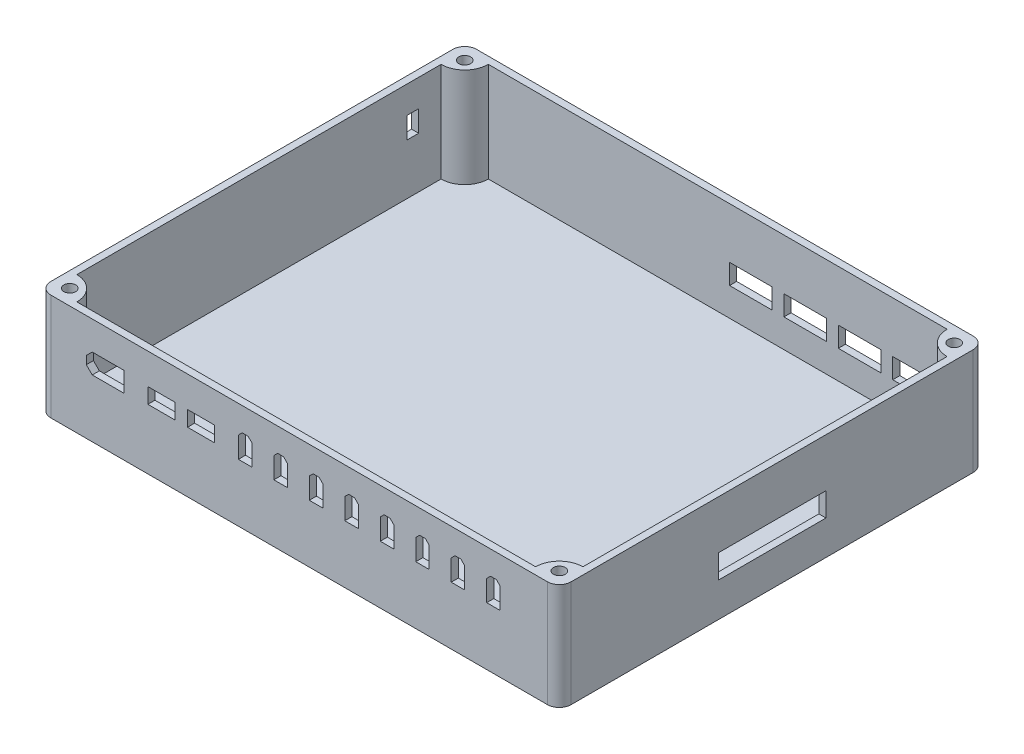
SolidWorks part; units mm, degrees
ref_plane "Front Plane" through (0, 0, 0) normal (0, 0, 1) x (1, 0, 0)
ref_plane "Top Plane" through (0, 0, 0) normal (0, 1, 0) x (1, 0, 0)
ref_plane "Right Plane" through (0, 0, 0) normal (1, 0, 0) x (0, 0, -1)
sketch "Sketch1" plane through (0, 0, 0) normal (0, 1, 0) x (1, 0, 0)
  line L1 (0, 0) -> (220, 0)
  line L2 (0, 0) -> (0, 180)
  line L3 (0, 180) -> (220, 180)
  line L4 (220, 0) -> (220, 180)
  dimension "D1" = 220
  dimension "D2" = 180
extrude "Boss-Extrude1" add sketch "Sketch1" along normal blind 45
fillet "Fillet1" radius 5 4 edges at (0, 22.5, -180) (0, 22.5, 0) (220, 22.5, -180) (220, 22.5, 0)
sketch "Sketch7" plane through (0, 45, 0) normal (0, 1, 0) x (1, 0, 0)
  line L0 (110, 187.4123) -> (110, -2.139) construction
  line L1 (-6.8646, 90) -> (231.1986, 90) construction
  line L2 (207, 177) -> (13, 177)
  line L3 (217, 167) -> (217, 13)
  line L4 (215, 180) -> (5, 180) construction
  line L5 (220, 5) -> (220, 175) construction
  line L6 (207, 3) -> (13, 3)
  line L7 (3, 167) -> (3, 13)
  line L8 (0, 175) -> (0, 5) construction
  line L9 (5, 0) -> (215, 0) construction
  arc A0 (207, 177) -> (217, 167) centre (217, 177) ccw
  arc A1 (207, 3) -> (217, 13) centre (217, 3) cw
  arc A2 (13, 3) -> (3, 13) centre (3, 3) ccw
  arc A3 (13, 177) -> (3, 167) centre (3, 177) cw
  point P14 (217, 90)
  point P18 (110, 3)
  point P23 (110, 177)
  dimension "D5" = 3
  dimension "D1" = 3
  dimension "D2" = 3
  dimension "D3" = 13
  dimension "D4" = 13
  dimension "D6" = 3
extrude "Cut-Extrude7" cut sketch "Sketch7" against normal blind 42
sketch "Sketch2" plane through (0, 0, 0) normal (0, 0, 1) x (1, 0, 0)
  line L0 (175.9, 35) -> (178.4, 35)
  line L1 (190.9, 35) -> (193.4, 35)
  line L2 (189.3, 33.4) -> (189.3, 24.5)
  line L3 (189.3, 24.5) -> (195, 24.5)
  line L4 (195, 33.4) -> (195, 24.5)
  line L5 (174.3, 33.4) -> (174.3, 24.5)
  line L6 (174.3, 24.5) -> (180, 24.5)
  line L7 (180, 33.4) -> (180, 24.5)
  line L8 (160.9, 35) -> (163.4, 35)
  line L9 (159.3, 33.4) -> (159.3, 24.5)
  line L10 (159.3, 24.5) -> (165, 24.5)
  line L11 (165, 33.4) -> (165, 24.5)
  line L12 (145.9, 35) -> (148.4, 35)
  line L13 (144.3, 33.4) -> (144.3, 24.5)
  line L14 (144.3, 24.5) -> (150, 24.5)
  line L15 (150, 33.4) -> (150, 24.5)
  line L16 (130.9, 35) -> (133.4, 35)
  line L17 (129.3, 33.4) -> (129.3, 24.5)
  line L18 (129.3, 24.5) -> (135, 24.5)
  line L19 (135, 33.4) -> (135, 24.5)
  line L20 (115.9, 35) -> (118.4, 35)
  line L21 (114.3, 33.4) -> (114.3, 24.5)
  line L22 (114.3, 24.5) -> (120, 24.5)
  line L23 (120, 33.4) -> (120, 24.5)
  line L24 (100.9, 35) -> (103.4, 35)
  line L25 (99.3, 33.4) -> (99.3, 24.5)
  line L26 (99.3, 24.5) -> (105, 24.5)
  line L27 (105, 33.4) -> (105, 24.5)
  line L28 (85.9, 35) -> (88.4, 35)
  line L29 (84.3, 33.4) -> (84.3, 24.5)
  line L30 (84.3, 24.5) -> (90, 24.5)
  line L31 (90, 33.4) -> (90, 24.5)
  line L33 (215, 0) -> (215, 45) construction
  line L35 (189.3, 33.4) -> (190.9, 35)
  line L36 (193.4, 35) -> (195, 33.4)
  line L37 (178.4, 35) -> (180, 33.4)
  line L38 (174.3, 33.4) -> (175.9, 35)
  line L39 (163.4, 35) -> (165, 33.4)
  line L40 (159.3, 33.4) -> (160.9, 35)
  line L41 (144.3, 33.4) -> (145.9, 35)
  line L42 (148.4, 35) -> (150, 33.4)
  line L43 (133.4, 35) -> (135, 33.4)
  line L44 (129.3, 33.4) -> (130.9, 35)
  line L45 (118.4, 35) -> (120, 33.4)
  line L46 (114.3, 33.4) -> (115.9, 35)
  line L47 (103.4, 35) -> (105, 33.4)
  line L48 (99.3, 33.4) -> (100.9, 35)
  line L49 (88.4, 35) -> (90, 33.4)
  line L50 (84.3, 33.4) -> (85.9, 35)
  point P0 (189.3, 35)
  point P3 (195, 35)
  point P6 (174.3, 35)
  point P9 (180, 35)
  point P10 (159.3, 35)
  point P13 (165, 35)
  point P14 (144.3, 35)
  point P17 (150, 35)
  point P18 (129.3, 35)
  point P21 (135, 35)
  point P22 (114.3, 35)
  point P25 (120, 35)
  point P26 (99.3, 35)
  point P29 (105, 35)
  point P30 (84.3, 35)
  point P33 (90, 35)
  dimension "D1" = 5.7
  dimension "D2" = 10.5
  dimension "D5" = 20
  dimension "D6" = 1.6
  dimension "D7" = 45
  dimension "D8" = 1.6
  dimension "D9" = 45
  dimension "D10" = 1.6
  dimension "D11" = 45
  dimension "D12" = 1.6
  dimension "D13" = 45
  dimension "D14" = 1.6
  dimension "D15" = 45
  dimension "D16" = 1.6
  dimension "D17" = 45
  dimension "D18" = 1.6
  dimension "D19" = 45
  dimension "D20" = 1.6
  dimension "D21" = 45
  dimension "D22" = 1.6
  dimension "D23" = 45
  dimension "D24" = 1.6
  dimension "D25" = 45
  dimension "D26" = 1.6
  dimension "D27" = 45
  dimension "D28" = 1.6
  dimension "D29" = 45
  dimension "D30" = 1.6
  dimension "D31" = 45
  dimension "D32" = 1.6
  dimension "D33" = 45
  dimension "D34" = 1.6
  dimension "D35" = 45
  dimension "D36" = 1.6
  dimension "D37" = 45
sketch "Sketch3" plane through (0, 0, 0) normal (0, 0, 1) x (1, 0, 0)
  line L0 (22.5, 32.9) -> (36, 32.9)
  line L1 (20, 30.4) -> (20, 27)
  line L2 (22.5, 24.5) -> (36, 24.5)
  line L3 (36, 32.9) -> (36, 24.5)
  line L4 (20, 30.4) -> (22.5, 32.9)
  line L5 (20, 27) -> (22.5, 24.5)
  line L6 (5, 0) -> (215, 0) construction
  line L7 (5, 45) -> (5, 0) construction
  point P0 (20, 32.9)
  point P2 (20, 24.5)
  dimension "D1" = 8.4
  dimension "D2" = 16
  dimension "D3" = 16
  dimension "D4" = 2.5
  dimension "D5" = 45
  dimension "D6" = 2.5
  dimension "D7" = 45
  dimension "D8" = 24.5
  dimension "D9" = 15
extrude "Cut-Extrude2" cut sketch "Sketch2" against normal blind 5
extrude "Cut-Extrude3" cut sketch "Sketch3" against normal blind 5
sketch "Sketch4" plane through (0, 0, 0) normal (0, 0, 1) x (1, 0, 0)
  line L0 (5, 0) -> (215, 0) construction
  line L1 (46, 25.5) -> (57.5, 25.5)
  line L2 (46, 25.5) -> (46, 32)
  line L3 (46, 32) -> (57.5, 32)
  line L4 (57.5, 25.5) -> (57.5, 32)
  line L5 (62.8, 25.5) -> (74.3, 25.5)
  line L6 (62.8, 25.5) -> (62.8, 32)
  line L7 (62.8, 32) -> (74.3, 32)
  line L8 (74.3, 25.5) -> (74.3, 32)
  line L9 (50.0473, 25.5) -> (65.0473, 25.5) construction
  line L10 (36, 24.5) -> (36, 32.9) construction
  line L11 (84.3, 33.4) -> (84.3, 24.5) construction
  dimension "D1" = 6.5
  dimension "D2" = 11.5
  dimension "D3" = 25.5
  dimension "D5" = 15
  dimension "D6" = 10
  dimension "D7" = 6.5
  dimension "D8" = 10
  dimension "D4" = 2
extrude "Cut-Extrude4" cut sketch "Sketch4" against normal blind 5
sketch "Sketch5" plane through (220, 0, 0) normal (1, 0, 0) x (0, 0, -1)
  line L0 (175, 0) -> (175, 45) construction
  line L5 (67.2316, 14.4802) -> (112.7684, 14.4802)
  line L7 (67.2316, 14.4802) -> (67.2316, 24.4802)
  line L8 (67.2316, 24.4802) -> (112.7684, 24.4802)
  line L9 (112.7684, 14.4802) -> (112.7684, 24.4802)
  line L10 (5, 45) -> (5, 0) construction
  dimension "D2" = 10
  dimension "D4" = 17.8646
extrude "Cut-Extrude5" cut sketch "Sketch5" against normal blind 5
sketch "Sketch6" plane through (0, 0, -180) normal (0, 0, -1) x (-1, 0, 0)
  line L0 (-215, 45) -> (-215, 0) construction
  line L1 (-202, 23.5) -> (-184, 23.5)
  line L2 (-202, 23.5) -> (-202, 15)
  line L3 (-202, 15) -> (-184, 15)
  line L4 (-184, 23.5) -> (-184, 15)
  line L5 (-215, 0) -> (-5, 0) construction
  line L6 (-179, 23.5) -> (-161, 23.5)
  line L7 (-179, 23.5) -> (-179, 15)
  line L8 (-179, 15) -> (-161, 15)
  line L9 (-161, 23.5) -> (-161, 15)
  line L10 (-156, 23.5) -> (-138, 23.5)
  line L11 (-156, 23.5) -> (-156, 15)
  line L12 (-156, 15) -> (-138, 15)
  line L13 (-138, 23.5) -> (-138, 15)
  line L14 (-133, 23.5) -> (-115, 23.5)
  line L15 (-133, 23.5) -> (-133, 15)
  line L16 (-133, 15) -> (-115, 15)
  line L17 (-115, 23.5) -> (-115, 15)
  line L18 (-202, 23.5) -> (-179, 23.5) construction
  dimension "D1" = 18
  dimension "D2" = 8.5
  dimension "D3" = 13
  dimension "D4" = 15
  dimension "D6" = 23
  dimension "D5" = 4
extrude "Cut-Extrude6" cut sketch "Sketch6" against normal blind 5
sketch "Sketch8" plane through (0, 0, 0) normal (-1, 0, 0) x (0, 0, 1)
  line L0 (-175, 0) -> (-5, 0) construction
  line L1 (-157.5384, 33.5) -> (-152.5384, 33.5)
  line L2 (-157.5384, 33.5) -> (-157.5384, 24.5)
  line L3 (-157.5384, 24.5) -> (-152.5384, 24.5)
  line L4 (-152.5384, 33.5) -> (-152.5384, 24.5)
  dimension "D1" = 9
  dimension "D2" = 5
  dimension "D3" = 24.5
extrude "Cut-Extrude8" cut sketch "Sketch8" against normal blind 4.2
sketch "Sketch10" plane through (0, 45, 0) normal (0, 1, 0) x (1, 0, 0)
  line L0 (110, 184.9025) -> (110, -6.3644) construction
  line L1 (-9.396, 90) -> (224.0695, 90) construction
  line L2 (0, 175) -> (0, 5) construction
  line L3 (110, -4.9025) -> (110, 186.3644) construction
  line L5 (215, 180) -> (5, 180) construction
  circle A0 centre (6.5, 173.5) radius 2.5
  circle A1 centre (213.5, 173.5) radius 2.5
  circle A2 centre (213.5, 6.5) radius 2.5
  circle A3 centre (6.5, 6.5) radius 2.5
  dimension "D1" = 6.5
  dimension "D3" = 5
  dimension "D2" = 6.5
extrude "Cut-Extrude9" cut sketch "Sketch10" against normal blind 40
equation "\"D8@Sketch4\"=\"D6@Sketch4\""
